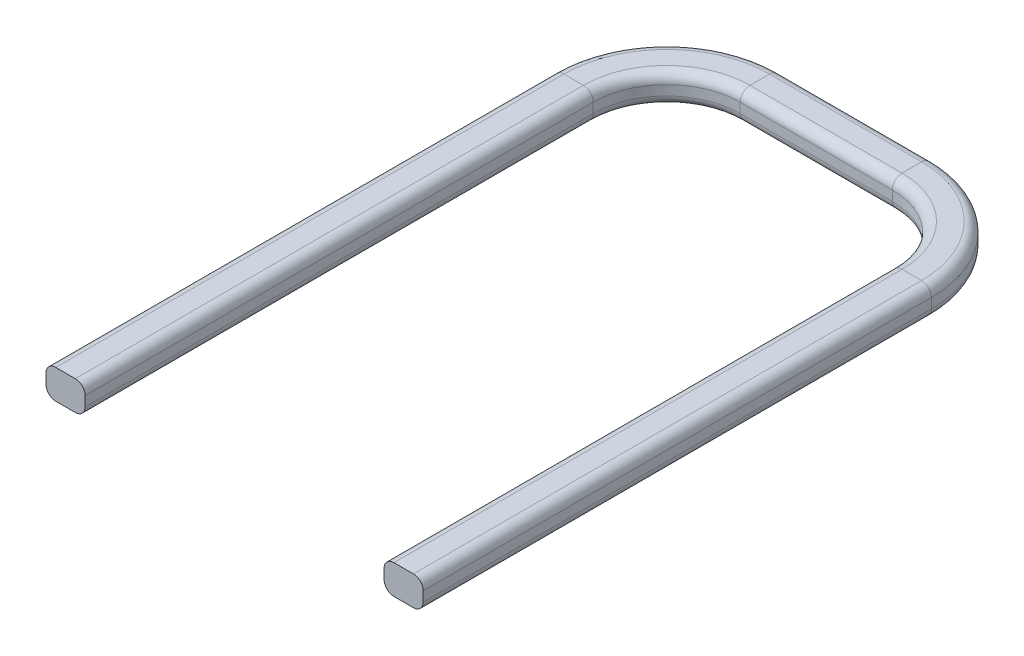
SolidWorks part; units mm, degrees
ref_plane "Front Plane" through (0, 0, 0) normal (0, 0, 1) x (1, 0, 0)
ref_plane "Top Plane" through (0, 0, 0) normal (0, 1, 0) x (1, 0, 0)
ref_plane "Right Plane" through (0, 0, 0) normal (1, 0, 0) x (0, 0, -1)
sketch "Sketch1" plane through (0, 0, 0) normal (0, 0, 1) x (1, 0, 0)
  line L1 (-0.5, 0.375) -> (0.5, 0.375)
  line L2 (-0.5, 0.375) -> (-0.5, -0.375)
  line L3 (-0.5, -0.375) -> (0.5, -0.375)
  line L4 (0.5, 0.375) -> (0.5, -0.375)
  line L5 (-0.5, 0.375) -> (0.5, -0.375) construction
  line L6 (-0.5, -0.375) -> (0.5, 0.375) construction
  point P0 (0, 0)
  dimension "D1" = 0.75
  dimension "D2" = 1
sketch "Sketch2" plane through (0, 0, 0) normal (0, 1, 0) x (1, 0, 0)
  line L0 (0, 0) -> (0, 13)
  line L1 (-0.5, 0) -> (0.5, 0) construction
  line L2 (2.38, 15.38) -> (6.27, 15.38)
  line L3 (8.65, 13) -> (8.65, 0)
  arc A0 (6.27, 15.38) -> (8.65, 13) centre (6.27, 13) cw
  arc A1 (0, 13) -> (2.38, 15.38) centre (2.38, 13) cw
  point P8 (8.65, 15.38)
  point P11 (0, 15.38)
  dimension "D3" = 2.38
  dimension "D1" = 15.38
  dimension "D2" = 8.65
sweep "Sweep1" add profiles "Sketch1" path "Sketch2"
fillet "Fillet1" radius 0.25 20 edges at (8.15, -0.375, -6.5) (7.5994, -0.375, -14.3294) (4.325, -0.375, -14.88) (1.0506, -0.375, -14.3294) (9.15, -0.375, -6.5) (8.3065, -0.375, -15.0365) (4.325, -0.375, -15.88) (0.3435, -0.375, -15.0365) (9.15, 0.375, -6.5) (8.3065, 0.375, -15.0365) (4.325, 0.375, -15.88) (0.3435, 0.375, -15.0365) (8.15, 0.375, -6.5) (7.5994, 0.375, -14.3294) (4.325, 0.375, -14.88) (1.0506, 0.375, -14.3294) (0.5, -0.375, -6.5) (-0.5, -0.375, -6.5) (-0.5, 0.375, -6.5) (0.5, 0.375, -6.5)
